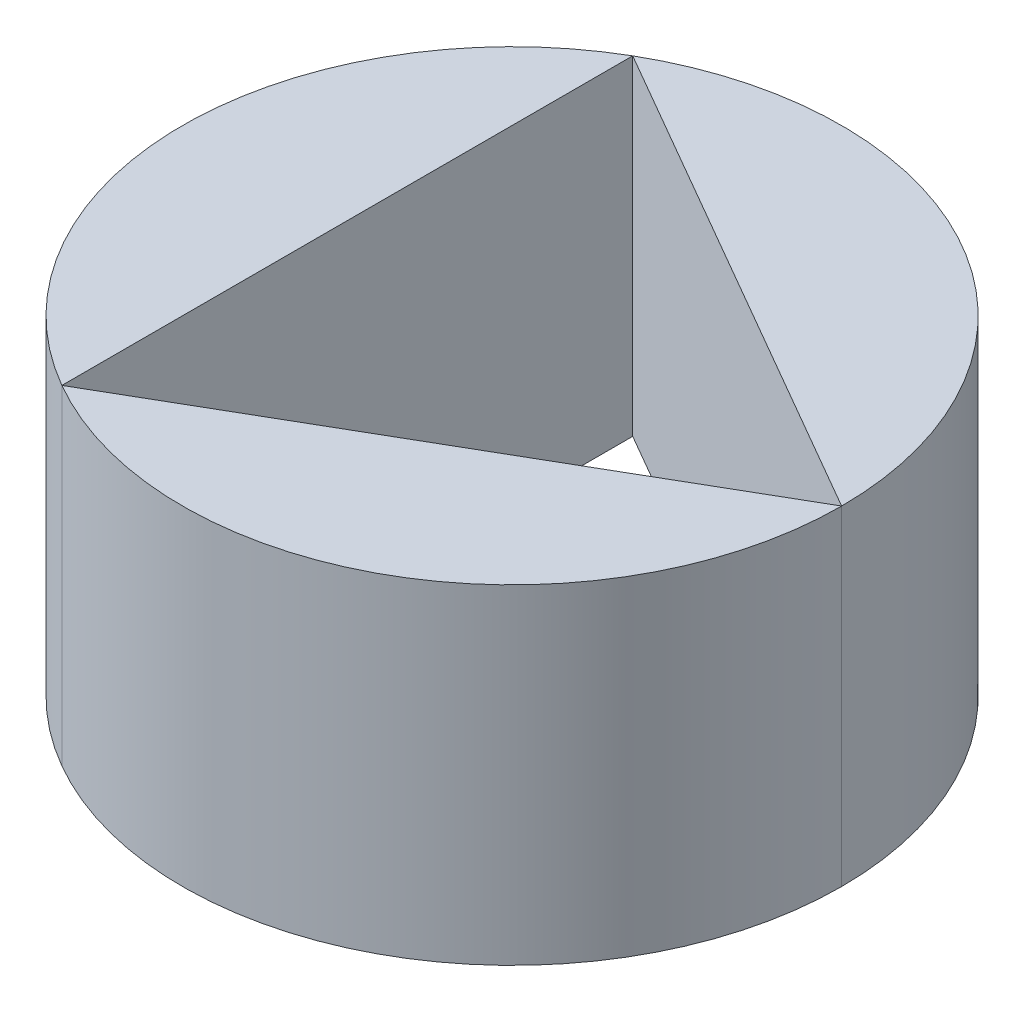
SolidWorks part; units mm, degrees
ref_plane "前视基准面" through (0, 0, 0) normal (0, 0, 1) x (1, 0, 0)
ref_plane "上视基准面" through (0, 0, 0) normal (0, 1, 0) x (1, 0, 0)
ref_plane "右视基准面" through (0, 0, 0) normal (1, 0, 0) x (0, 0, -1)
sketch "草图1" plane through (0, 0, 0) normal (0, 1, 0) x (1, 0, 0)
  circle A0 centre (0, 0) radius 30
  point P2 (0, 0)
  dimension "D1" = 60
extrude "凸台-拉伸1" add sketch "草图1" along normal blind 30
sketch "草图2" plane through (0, 30, 0) normal (0, 1, 0) x (1, 0, 0)
  line L1 (30, 0) -> (-15, 25.9808)
  line L2 (-15, 25.9808) -> (-15, -25.9808)
  line L3 (-15, -25.9808) -> (30, 0)
  circle A0 centre (0, 0) radius 15 construction
  point P1 (0, 0)
extrude "切除-拉伸1" cut sketch "草图2" against normal through all
